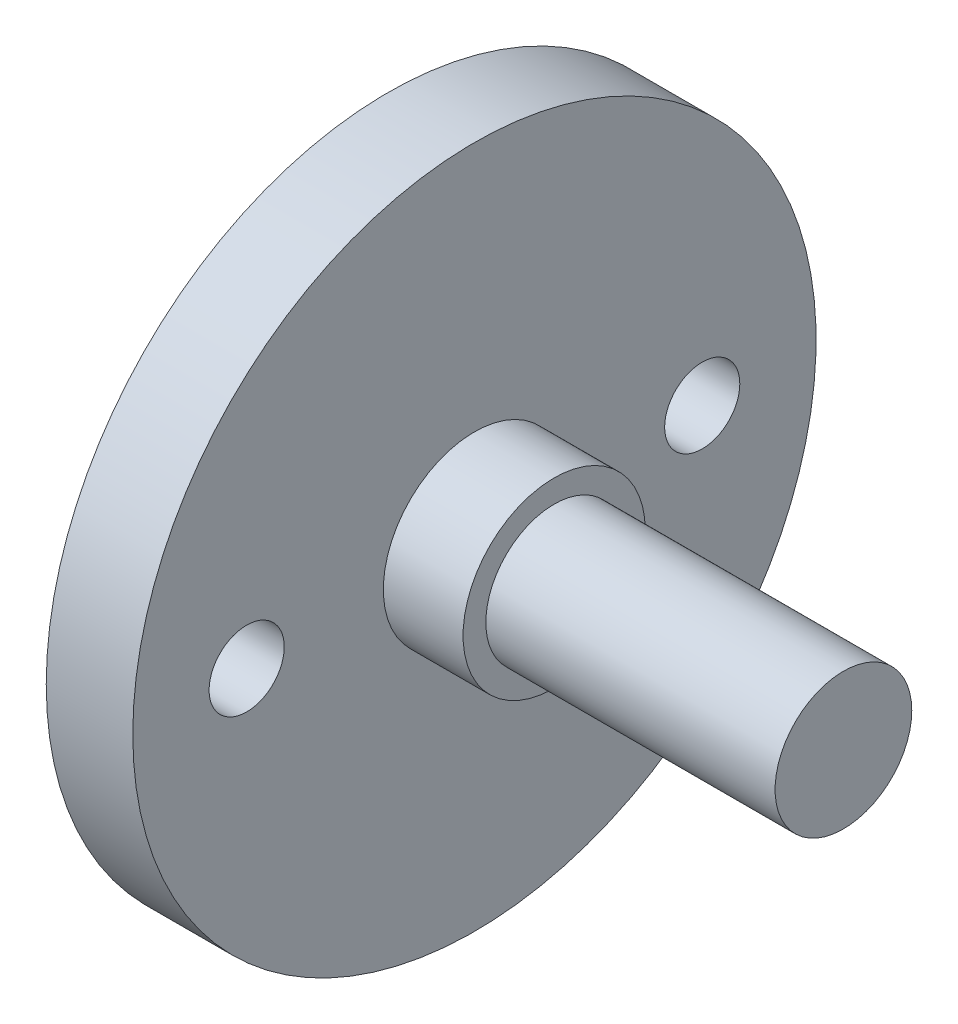
SolidWorks part; units mm, degrees
material "1060 合金"
ref_plane "正面" through (0, 0, 0) normal (0, 0, 1) x (1, 0, 0)
ref_plane "平面" through (0, 0, 0) normal (0, 1, 0) x (1, 0, 0)
ref_plane "右側面" through (0, 0, 0) normal (1, 0, 0) x (0, 0, -1)
sketch "ｽｹｯﾁ1" plane through (0, 0, 0) normal (1, 0, 0) x (0, 0, -1)
  circle A0 centre (0, 0) radius 15
  dimension "D1" = 30
extrude "ﾎﾞｽ - 押し出し1" add sketch "ｽｹｯﾁ1" along normal blind 10.8
sketch "ｽｹｯﾁ2" plane through (10.8, 0, 0) normal (1, 0, 0) x (0, 0, -1)
  circle A0 centre (0, 0) radius 4
  dimension "D1" = 8
extrude "ﾎﾞｽ - 押し出し2" add sketch "ｽｹｯﾁ2" along normal blind 3.5
sketch "ｽｹｯﾁ3" plane through (14.3, 0, 0) normal (1, 0, 0) x (0, 0, -1)
  circle A0 centre (0, 0) radius 3
  dimension "D1" = 6
extrude "ﾎﾞｽ - 押し出し3" add sketch "ｽｹｯﾁ3" along normal blind 5.8
sketch "ｽｹｯﾁ4" plane through (0, 0, 0) normal (-1, 0, 0) x (0, 0, 1)
  line L0 (0, 0) -> (50000, 0) construction
  line L1 (0, 0) -> (0, 50000) construction
  circle A0 centre (10, 0) radius 1.65
  circle A1 centre (-10, 0) radius 1.65
  dimension "D1" = 20
  dimension "D2" = 3.3
extrude "ｶｯﾄ - 押し出し1" cut sketch "ｽｹｯﾁ4" against normal through all
sketch "ｽｹｯﾁ5" plane through (20.1, 0, 0) normal (1, 0, 0) x (0, 0, -1)
  circle A0 centre (0, 0) radius 3
  dimension "D1" = 6
extrude "ﾎﾞｽ - 押し出し4" add sketch "ｽｹｯﾁ5" along normal blind 6.9
sketch "ｽｹｯﾁ6" plane through (0, 0, 0) normal (-1, 0, 0) x (0, 0, 1)
  circle A0 centre (0, 0) radius 15
extrude "ｶｯﾄ - 押し出し2" cut sketch "ｽｹｯﾁ6" against normal blind 7
